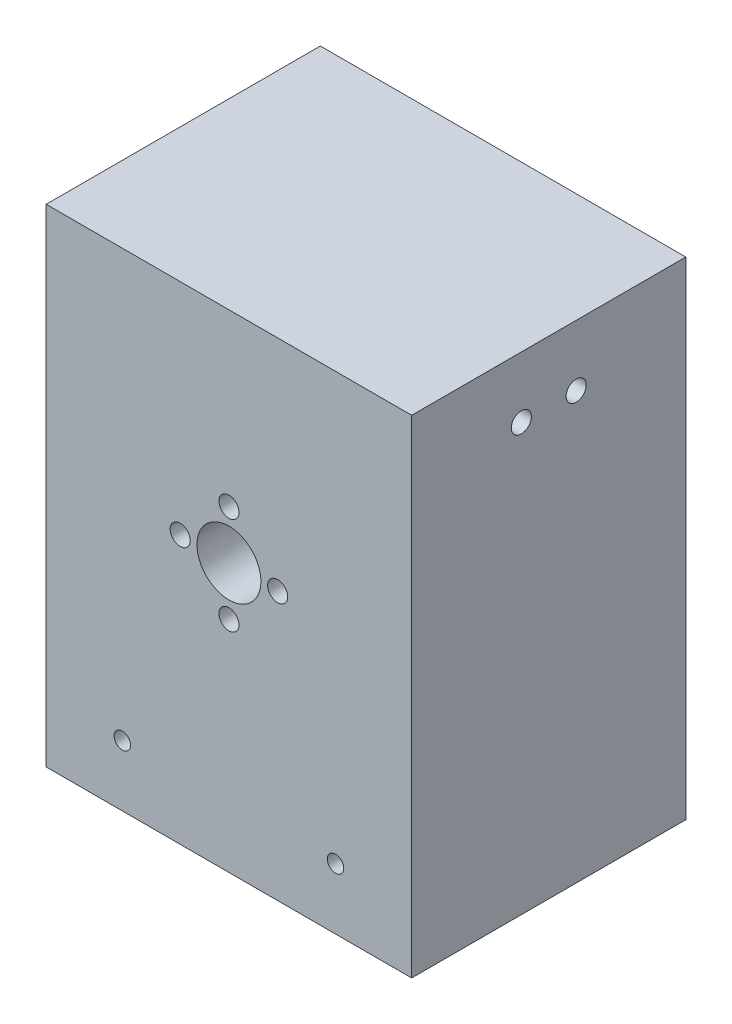
SolidWorks part; units mm, degrees
ref_plane "前视基准面" through (0, 0, 0) normal (0, 0, 1) x (1, 0, 0)
ref_plane "上视基准面" through (0, 0, 0) normal (0, 1, 0) x (1, 0, 0)
ref_plane "右视基准面" through (0, 0, 0) normal (1, 0, 0) x (0, 0, -1)
sketch "草图1" plane through (0, 0, 0) normal (0, 0, 1) x (1, 0, 0)
  line L1 (-30, -40) -> (30, -40)
  line L2 (-30, -40) -> (-30, 40)
  line L3 (-30, 40) -> (30, 40)
  line L4 (30, -40) -> (30, 40)
  line L5 (-30, -40) -> (30, 40) construction
  line L6 (-30, 40) -> (30, -40) construction
  point P0 (0, 0)
  dimension "D1" = 60
  dimension "D2" = 80
extrude "凸台-拉伸1" add sketch "草图1" along normal blind 45
sketch "草图2" plane through (0, 0, 45) normal (0, 0, 1) x (1, 0, 0)
  line L0 (-62.5397, -30) -> (50.7554, -30) construction
  line L1 (0, 12.9827) -> (0, -55.3897) construction
  line L2 (-30, -40) -> (30, -40) construction
  circle A0 centre (17.5, -30) radius 1.35
  circle A1 centre (-17.5, -30) radius 1.35
  dimension "D1" = 2.7
  dimension "D2" = 2.7
  dimension "D3" = 17.5
  dimension "D4" = 35
  dimension "D5" = 10
extrude "切除-拉伸1" cut sketch "草图2" against normal blind 100
sketch "草图3" plane through (0, 0, 45) normal (0, 0, 1) x (1, 0, 0)
  line L0 (-30, -40) -> (30, -40) construction
  circle A0 centre (0, 4) radius 8 construction
  circle A1 centre (8, 4) radius 1.65
  circle A2 centre (0, 12) radius 1.65
  circle A3 centre (-8, 4) radius 1.65
  circle A4 centre (0, -4) radius 1.65
  dimension "D1" = 16
  dimension "D2" = 3.3
  dimension "D3" = 3.3
  dimension "D4" = 3.3
  dimension "D5" = 3.3
  dimension "D6" = 44
extrude "切除-拉伸2" cut sketch "草图3" against normal blind 100
sketch "草图4" plane through (0, 0, 45) normal (0, 0, 1) x (1, 0, 0)
  circle A0 centre (0, 4) radius 5.25
  dimension "D1" = 10.5
extrude "切除-拉伸3" cut sketch "草图4" against normal blind 1000
sketch "草图5" plane through (0, -40, 0) normal (0, -1, 0) x (1, 0, 0)
  line L0 (-30, 22.5) -> (30, 22.5) construction
  line L1 (-30, 45) -> (-30, 0) construction
  line L2 (30, 45) -> (30, 0) construction
  line L3 (0, 45) -> (0, 0) construction
  line L4 (1.65, 45) -> (-1.65, 45) construction
  line L5 (-30, 45) -> (30, 45) construction
  line L6 (-24, 6) -> (24, 6)
  line L7 (-24, 6) -> (-24, 39)
  line L8 (-24, 39) -> (24, 39)
  line L9 (24, 6) -> (24, 39)
  line L10 (-24, 6) -> (24, 39) construction
  line L11 (-24, 39) -> (24, 6) construction
  point P11 (0, 22.5)
  dimension "D1" = 6
  dimension "D2" = 6
extrude "切除-拉伸4" cut sketch "草图5" against normal blind 25
sketch "草图6" plane through (30, 0, 0) normal (1, 0, 0) x (0, 0, -1)
  line L0 (-50.4455, 30) -> (10.8276, 30) construction
  line L1 (-45, 40) -> (0, 40) construction
  line L2 (-22.5, 40) -> (-22.5, -46.3171) construction
  circle A0 centre (-18, 30) radius 1.65
  circle A1 centre (-27, 30) radius 1.65
  dimension "D4" = 3.3
  dimension "D5" = 3.3
  dimension "D1" = 10
  dimension "D2" = 4.5
  dimension "D3" = 4.5
extrude "切除-拉伸5" cut sketch "草图6" against normal blind 5000
